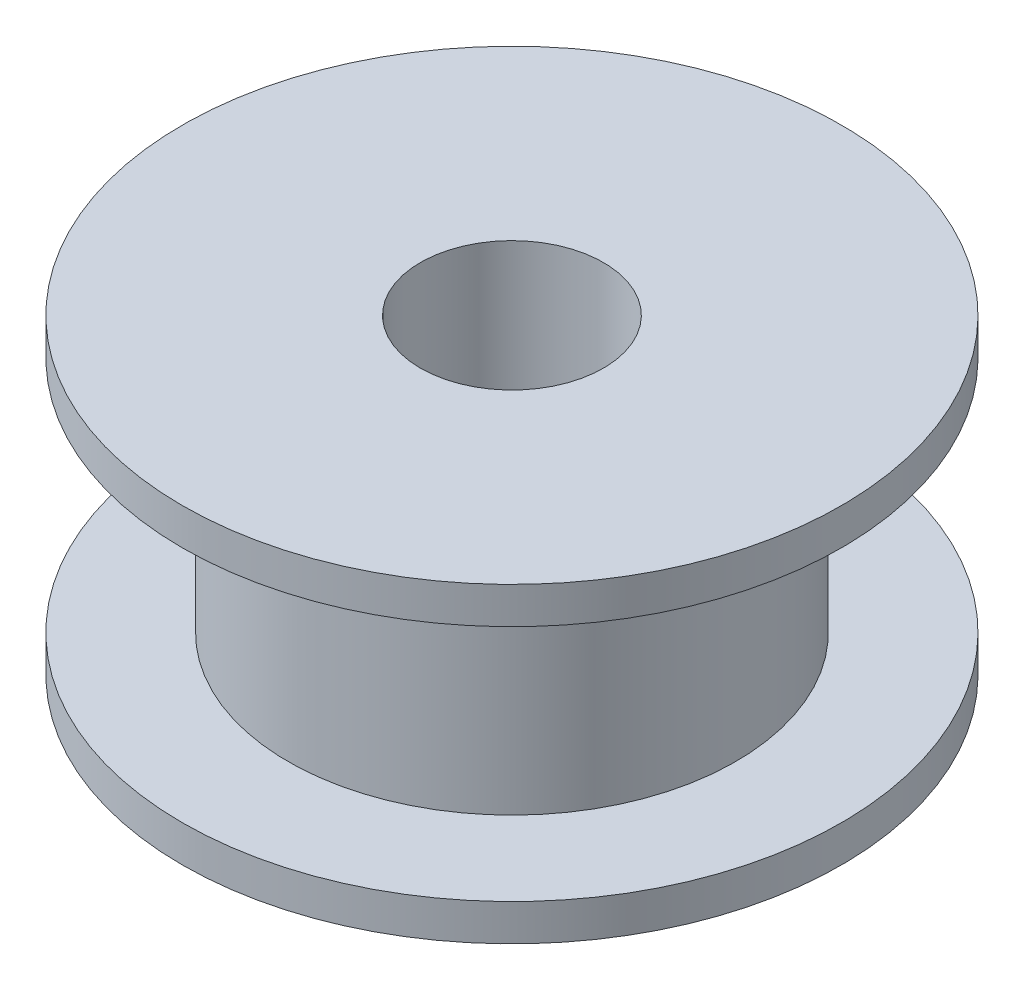
SolidWorks part; units mm, degrees
material "1060 合金"
ref_plane "前视基准面" through (0, 0, 0) normal (0, 0, 1) x (1, 0, 0)
ref_plane "上视基准面" through (0, 0, 0) normal (0, 1, 0) x (1, 0, 0)
ref_plane "右视基准面" through (0, 0, 0) normal (1, 0, 0) x (0, 0, -1)
other "Configuration Table"
sketch "草图1" plane through (0, 0, 0) normal (0, 1, 0) x (1, 0, 0)
  circle A0 centre (0, 0) radius 9
  dimension "D1" = 18
extrude "凸台-拉伸1" add sketch "草图1" along normal blind 1
sketch "草图2" plane through (0, 1, 0) normal (0, 1, 0) x (1, 0, 0)
  circle A0 centre (0, 0) radius 6.11
  dimension "D1" = 12.22
extrude "凸台-拉伸2" add sketch "草图2" along normal blind 6.5
sketch "草图3" plane through (0, 7.5, 0) normal (0, 1, 0) x (1, 0, 0)
  circle A0 centre (0, 0) radius 9
  dimension "D1" = 18
extrude "凸台-拉伸3" add sketch "草图3" along normal blind 1
sketch "草图4" plane through (0, 8.5, 0) normal (0, 1, 0) x (1, 0, 0)
  circle A0 centre (0, 0) radius 2.5
  dimension "D1" = 5
extrude "切除-拉伸1" cut sketch "草图4" against normal blind 13
